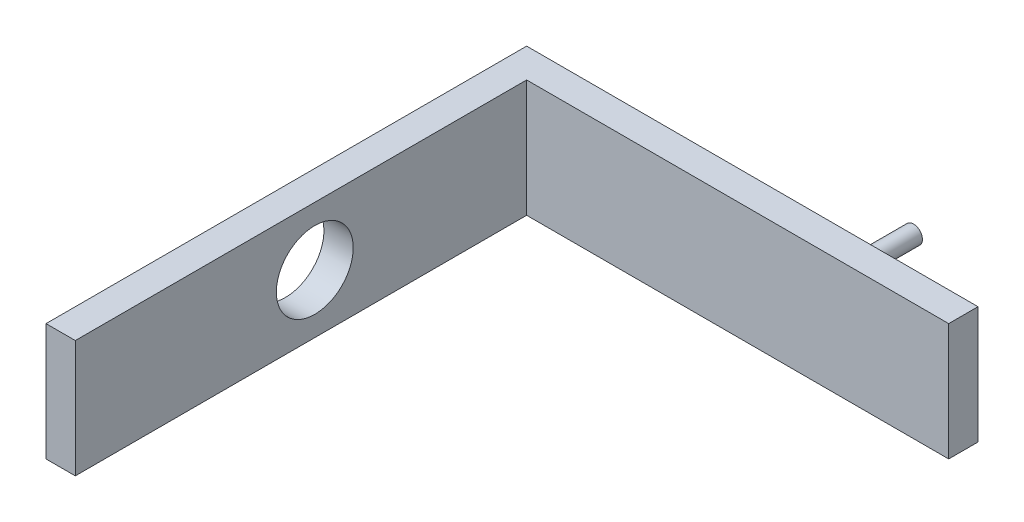
SolidWorks part; units mm, degrees
ref_plane "Front Plane" through (0, 0, 0) normal (0, 0, 1) x (1, 0, 0)
ref_plane "Top Plane" through (0, 0, 0) normal (0, 1, 0) x (1, 0, 0)
ref_plane "Right Plane" through (0, 0, 0) normal (1, 0, 0) x (0, 0, -1)
sketch "Sketch1" plane through (0, 0, 0) normal (0, 1, 0) x (1, 0, 0)
  line L1 (-2.7577, -19.8611) -> (1.211, -19.8611)
  line L2 (-2.7577, -19.8611) -> (-2.7577, 45.2264)
  line L3 (-2.7577, 45.2264) -> (6.2797, 45.2264)
  line L4 (1.211, -19.8611) -> (1.211, 41.2577)
  line L5 (-2.7577, -19.8611) -> (6.2797, 45.2264) construction
  line L6 (-2.7577, 45.2264) -> (1.211, -19.8611) construction
  line L7 (6.2797, 45.2264) -> (58.361, 45.2264)
  line L9 (1.211, 41.2577) -> (58.361, 41.2577)
  line L10 (58.361, 45.2264) -> (58.361, 41.2577)
  point P0 (0, 0)
  dimension "D1" = 3.9688
  dimension "D2" = 3.9688
  dimension "D3" = 57.15
  dimension "D4" = 61.1187
extrude "Boss-Extrude1" add sketch "Sketch1" along normal mid plane 15.875
sketch "Sketch3" plane through (-2.7577, 0, 0) normal (-1, 0, 0) x (0, 0, 1)
  circle A0 centre (-12.5666, 0) radius 5.207
  dimension "D1" = 10.414
extrude "Cut-Extrude1" cut sketch "Sketch3" against normal up to surface (3.9688 mm away) up to face at (1.211, 0, -10.6983)
sketch "Sketch4" plane through (0, 0, -45.2264) normal (0, 0, -1) x (-1, 0, 0)
  line L0 (2.7577, 7.9375) -> (2.7577, -7.9375) construction
  circle A0 centre (-37.5648, 0) radius 1.2065
  dimension "D1" = 2.413
  dimension "D2" = 40.3225
extrude "Boss-Extrude2" add sketch "Sketch4" along normal blind 12.065
